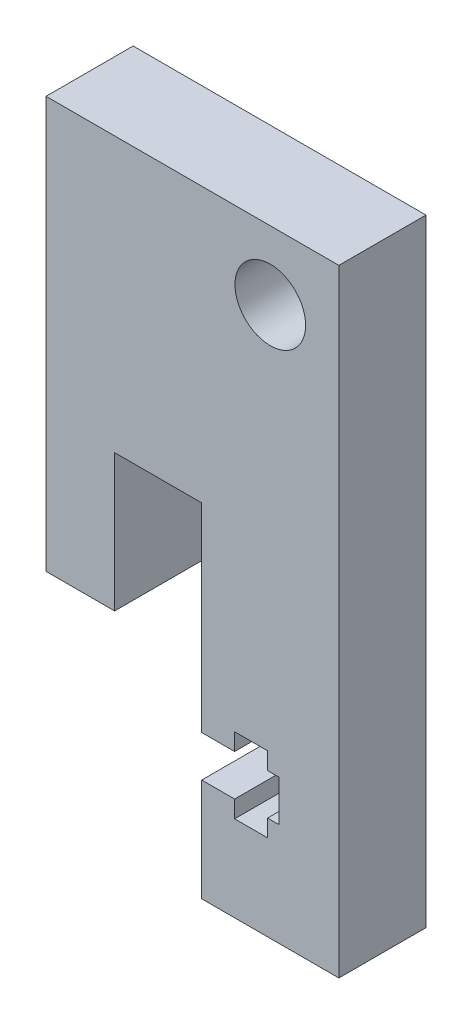
SolidWorks part; units mm, degrees
ref_plane "Front Plane" through (0, 0, 0) normal (0, 0, 1) x (1, 0, 0)
ref_plane "Top Plane" through (0, 0, 0) normal (0, 1, 0) x (1, 0, 0)
ref_plane "Right Plane" through (0, 0, 0) normal (1, 0, 0) x (0, 0, -1)
sketch "Sketch1" plane through (0, 0, 0) normal (0, 0, 1) x (1, 0, 0)
  line L1 (8.5406, 34.2167) -> (8.5406, -10.7833)
  line L2 (8.5406, -10.7833) -> (-1.4594, -10.7833)
  line L3 (-1.4594, -10.7833) -> (-1.4594, 14.2167)
  line L4 (-1.4594, 14.2167) -> (-7.8094, 14.2167)
  line L5 (-7.8094, 14.2167) -> (-7.8094, 4.2167)
  line L6 (-7.8094, 4.2167) -> (-12.8094, 4.2167)
  line L7 (-12.8094, 4.2167) -> (-12.8094, 34.2167)
  line L9 (-12.8094, 34.2167) -> (8.5406, 34.2167)
  line L10 (-1.4594, -0.2833) -> (0.9406, -0.2833)
  line L11 (0.9406, -0.2833) -> (0.9406, 0.9667)
  line L12 (0.9406, 0.9667) -> (3.3406, 0.9667)
  line L13 (3.3406, 0.9667) -> (3.3406, -0.2833)
  line L14 (3.3406, -0.2833) -> (4.1906, -0.2833)
  line L15 (4.1906, -0.2833) -> (4.1906, -3.2833)
  line L16 (4.1906, -3.2833) -> (3.3406, -3.2833)
  line L17 (3.3406, -3.2833) -> (3.3406, -4.5333)
  line L18 (3.3406, -4.5333) -> (0.9406, -4.5333)
  line L19 (0.9406, -4.5333) -> (0.9406, -3.2833)
  line L20 (0.9406, -3.2833) -> (-1.4594, -3.2833)
  circle A0 centre (3.5406, 29.2167) radius 2.575
  point P20 (4.1906, -1.7833)
  point P23 (0, 0)
  point P24 (0, 0)
  point P25 (0, 0)
  point P26 (0, 0)
  dimension "D15" = 5.15
  dimension "D1" = 10
  dimension "D2" = 3
  dimension "D3" = 5.5
  dimension "D4" = 2.75
  dimension "D5" = 2.4
  dimension "D6" = 5.65
  dimension "D7" = 7.5
  dimension "D8" = 45
  dimension "D9" = 2.4
  dimension "D10" = 6.35
  dimension "D11" = 5
  dimension "D12" = 10
  dimension "D13" = 25
  dimension "D14" = 5
  dimension "D16" = 5
extrude "Boss-Extrude1" add sketch "Sketch1" along normal blind 6.35 contours L19 L20 L3 L2 L1 L9 L7 L6 L5 L4 L10 L11 L12 L13 L14 L15 L16 L17 L18 A0
